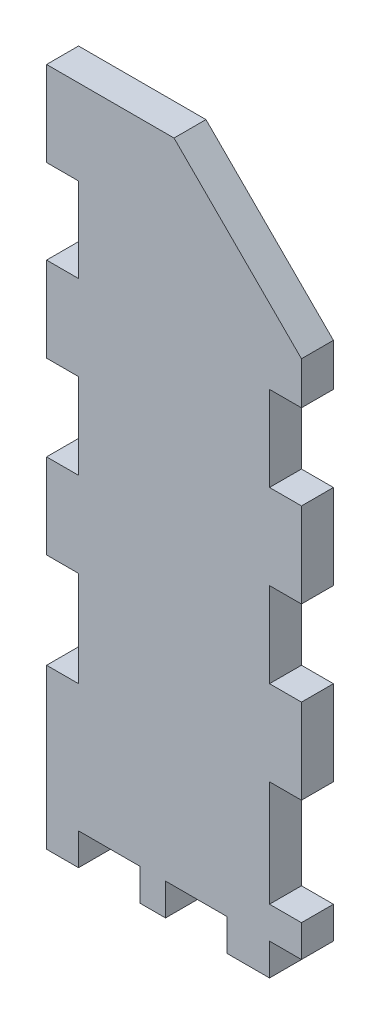
SolidWorks part; units mm, degrees
ref_plane "Front Plane" through (0, 0, 0) normal (0, 0, 1) x (1, 0, 0)
ref_plane "Top Plane" through (0, 0, 0) normal (0, 1, 0) x (1, 0, 0)
ref_plane "Right Plane" through (0, 0, 0) normal (1, 0, 0) x (0, 0, -1)
sketch "Sketch2" plane through (0, 0, 0) normal (0, 0, 1) x (1, 0, 0)
  line L0 (0, 0) -> (0, 101.6)
  line L1 (0, 0) -> (38.1, 0)
  line L2 (38.1, 0) -> (38.1, 82.55)
  line L3 (0, 101.6) -> (19.05, 101.6)
  line L4 (19.05, 101.6) -> (38.1, 82.55)
  line L5 (0, 0) -> (6.4723, 0) construction
  point P3 (0, 0)
  dimension "D1" = 38.1
  dimension "D2" = 101.6
  dimension "D3" = 82.55
  dimension "D4" = 19.05
extrude "Boss-Extrude1" add sketch "Sketch2" along normal blind 4.7752 contours L4 L2 L1 L0 L3
sketch "Sketch3" plane through (0, 0, 4.7752) normal (0, 0, 1) x (1, 0, 0)
  line L0 (4.7752, 0) -> (13.97, 0)
  line L1 (0, 0) -> (38.1, 0) construction
  line L2 (0, 0) -> (4.7752, 0)
  line L3 (0, 0) -> (0, 4.7752)
  line L4 (0, 4.7752) -> (4.7752, 4.7752)
  line L5 (4.7752, 0) -> (4.7752, 4.7752)
  line L7 (13.97, 0) -> (17.78, 0)
  line L8 (13.97, 0) -> (13.97, 4.7752)
  line L9 (13.97, 4.7752) -> (17.78, 4.7752)
  line L10 (17.78, 0) -> (17.78, 4.7752)
  line L11 (26.9748, 0) -> (33.3248, 0)
  line L12 (26.9748, 0) -> (26.9748, 4.7752)
  line L13 (26.9748, 4.7752) -> (33.3248, 4.7752)
  line L14 (33.3248, 0) -> (33.3248, 4.7752)
  line L15 (4.7752, 4.7752) -> (13.97, 4.7752)
  line L16 (4.7752, 4.7752) -> (4.7752, 0)
  line L17 (4.7752, 0) -> (13.97, 0)
  line L18 (13.97, 4.7752) -> (13.97, 0)
  line L20 (17.78, 4.7752) -> (26.9748, 4.7752)
  line L21 (17.78, 4.7752) -> (17.78, 0)
  line L22 (17.78, 0) -> (26.9748, 0)
  line L23 (26.9748, 4.7752) -> (26.9748, 0)
  line L24 (33.3248, 4.7752) -> (38.1, 4.7752)
  line L25 (33.3248, 4.7752) -> (33.3248, 0)
  line L26 (33.3248, 0) -> (38.1, 0)
  line L27 (38.1, 4.7752) -> (38.1, 0)
  dimension "D1" = 4.7752
  dimension "D2" = 4.7752
  dimension "D3" = 3.81
  dimension "D4" = 9.1948
  dimension "D5" = 9.1948
  dimension "D6" = 6.35
extrude "Cut-Extrude4" cut sketch "Sketch3" against normal blind 6.35 contours L15 L5 L8 | L20 L10 L15 L12 | L24 L14 L15 L16
sketch "Sketch4" plane through (0, 0, 4.7752) normal (0, 0, 1) x (1, 0, 0)
  line L0 (0, 0) -> (0, 101.6) construction
  line L1 (0, 50.8) -> (4.7752, 50.8)
  line L2 (0, 50.8) -> (0, 63.575)
  line L3 (0, 63.575) -> (4.7752, 63.575)
  line L4 (4.7752, 50.8) -> (4.7752, 63.575)
  line L5 (38.1, 4.7752) -> (38.1, 82.55) construction
  line L6 (38.1, 50.8) -> (33.3248, 50.8)
  line L7 (38.1, 50.8) -> (38.1, 38.1)
  line L8 (38.1, 38.1) -> (33.3248, 38.1)
  line L9 (33.3248, 50.8) -> (33.3248, 38.1)
  line L10 (0, 101.6) -> (19.05, 101.6) construction
  line L11 (0, 38.1) -> (4.7752, 38.1)
  line L12 (0, 38.1) -> (0, 23.8252)
  line L13 (0, 23.8252) -> (4.7752, 23.8252)
  line L14 (4.7752, 38.1) -> (4.7752, 23.8252)
  line L15 (38.1, 25.4) -> (33.3248, 25.4)
  line L16 (38.1, 25.4) -> (38.1, 9.5504)
  line L17 (38.1, 9.5504) -> (33.3248, 9.5504)
  line L18 (33.3248, 25.4) -> (33.3248, 9.5504)
  line L19 (38.1, 63.5) -> (33.3248, 63.5)
  line L20 (38.1, 63.5) -> (38.1, 76.2)
  line L21 (38.1, 76.2) -> (33.3248, 76.2)
  line L22 (33.3248, 63.5) -> (33.3248, 76.2)
  line L23 (0, 76.275) -> (4.7752, 76.275)
  line L24 (0, 76.275) -> (0, 88.9)
  line L25 (0, 88.9) -> (4.7752, 88.9)
  line L26 (4.7752, 76.275) -> (4.7752, 88.9)
  line L27 (4.7752, 4.7752) -> (13.97, 4.7752) construction
  line L28 (33.3248, 4.7752) -> (38.1, 4.7752) construction
  point P28 (2.3876, 38.1)
  point P33 (35.7124, 9.5504)
  point P36 (35.7124, 63.5)
  dimension "D1" = 4.7752
  dimension "D2" = 4.7752
  dimension "D3" = 4.7752
  dimension "D4" = 4.7752
  dimension "D5" = 4.7752
  dimension "D6" = 4.7752
  dimension "D7" = 12.7
  dimension "D8" = 12.7
  dimension "D9" = 12.7
  dimension "D10" = 19.05
  dimension "D11" = 4.7752
  dimension "D12" = 12.7
  dimension "D13" = 12.7
  dimension "D14" = 6.35
  dimension "D15" = 12.7
  dimension "D16" = 12.7
extrude "Cut-Extrude5" cut sketch "Sketch4" against normal blind 6.35
sketch "Sketch5" plane through (0, 0, 4.7752) normal (0, 0, 1) x (1, 0, 0)
